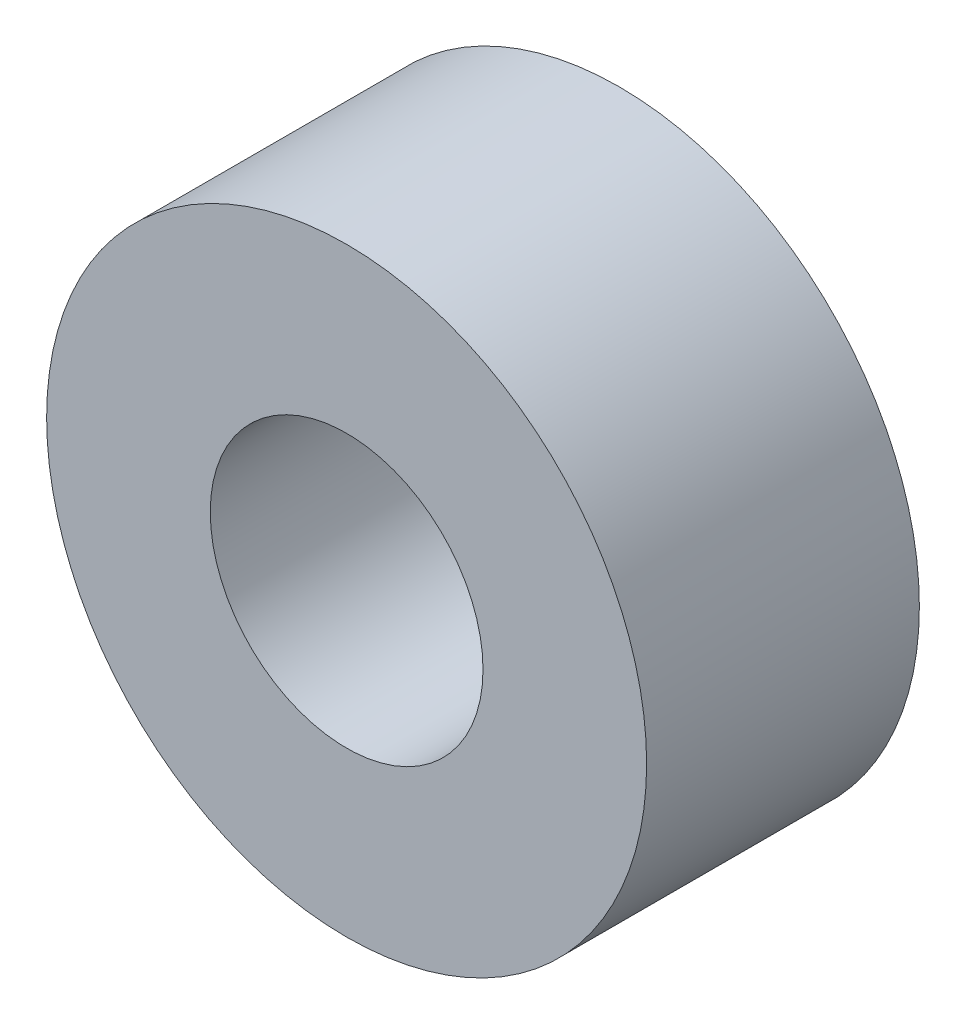
SolidWorks part; units mm, degrees
ref_plane "Front" through (0, 0, 0) normal (0, 0, 1) x (1, 0, 0)
ref_plane "Top" through (0, 0, 0) normal (0, 1, 0) x (1, 0, 0)
ref_plane "Right" through (0, 0, 0) normal (1, 0, 0) x (0, 0, -1)
sketch "Эскиз1" plane through (0, 0, 0) normal (0, 0, 1) x (1, 0, 0)
  circle A0 centre (0, 0) radius 2.5
  circle A1 centre (0, 0) radius 5.5
  dimension "D1" = 11
  dimension "D2" = 5
extrude "Бобышка-Вытянуть1" add sketch "Эскиз1" along normal mid plane 5
